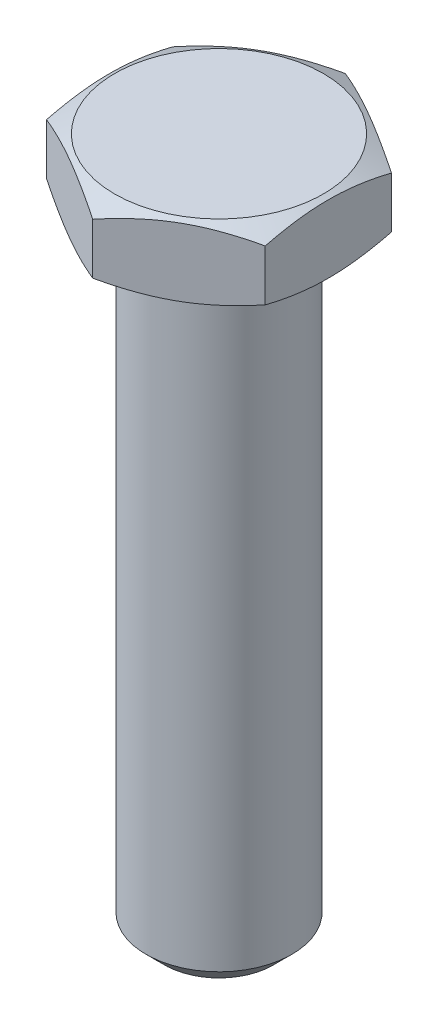
SolidWorks part; units mm, degrees
ref_plane "Front Plane" through (0, 0, 0) normal (0, 0, 1) x (1, 0, 0)
ref_plane "Top Plane" through (0, 0, 0) normal (0, 1, 0) x (1, 0, 0)
ref_plane "Right Plane" through (0, 0, 0) normal (1, 0, 0) x (0, 0, -1)
sketch "Sketch1" plane through (0, 0, 0) normal (0, 1, 0) x (1, 0, 0)
  line L1 (0, -3.4641) -> (3, -1.7321)
  line L2 (3, -1.7321) -> (3, 1.7321)
  line L3 (3, 1.7321) -> (0, 3.4641)
  line L4 (0, 3.4641) -> (-3, 1.7321)
  line L5 (-3, 1.7321) -> (-3, -1.7321)
  line L6 (-3, -1.7321) -> (0, -3.4641)
  circle A0 centre (0, 0) radius 3 construction
  dimension "D1" = 6
extrude "Boss-Extrude1" add sketch "Sketch1" along normal blind 2
sketch "Sketch2" plane through (0, 0, 0) normal (0, -1, 0) x (1, 0, 0)
  circle A0 centre (0, 0) radius 2
extrude "Boss-Extrude2" add sketch "Sketch2" along normal blind 17
chamfer "Chamfer1" distance 0.5 angle 45 1 edges at (0, -17, -2)
sketch "Sketch4" plane through (0, 0, 0) normal (1, 0, 0) x (0, 0, -1)
  line L0 (-2.8641, 2) -> (-3.4641, 1.7)
  line L1 (-3.4641, 2) -> (-1.7321, 2) construction
  line L2 (-3.4641, 2) -> (-3.4641, 0) construction
  line L3 (-3.4641, 1.7) -> (-3.4641, 2)
  line L4 (-3.4641, 2) -> (-2.8641, 2)
  line L5 (-3.4641, 0) -> (-2.8641, 0)
  line L6 (-2.8641, 0) -> (-3.4641, 0.3)
  line L7 (0, 2) -> (0, 5.3794) construction
  line L8 (-3.4641, 0.3) -> (-3.4641, 0)
  dimension "D1" = 0.6
  dimension "D2" = 0.3
  dimension "D3" = 0.6
  dimension "D4" = 0.3
revolve "Cut-Revolve2" cut sketch "Sketch4" angle 360 about L7
